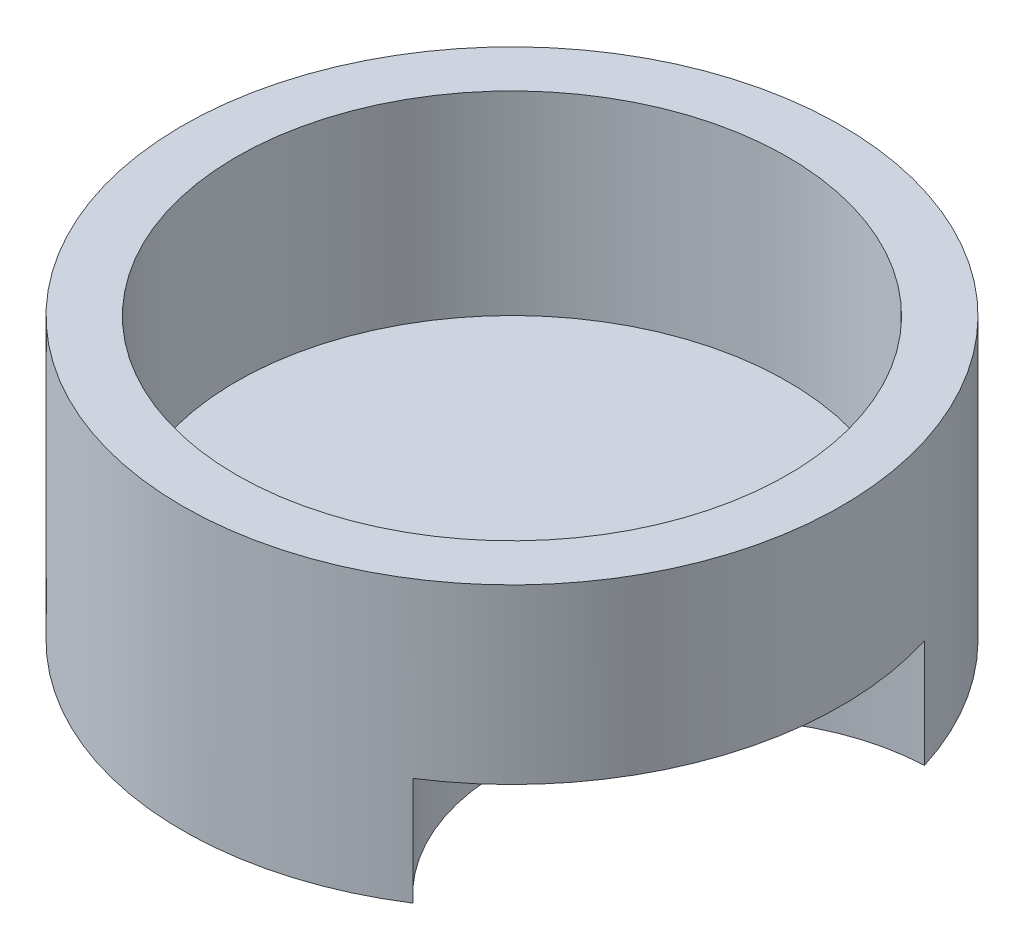
SolidWorks part; units mm, degrees
ref_plane "前视基准面" through (0, 0, 0) normal (0, 0, 1) x (1, 0, 0)
ref_plane "上视基准面" through (0, 0, 0) normal (0, 1, 0) x (1, 0, 0)
ref_plane "右视基准面" through (0, 0, 0) normal (1, 0, 0) x (0, 0, -1)
other "Configuration Table"
sketch "草图1" plane through (0, 0, 0) normal (0, 1, 0) x (1, 0, 0)
  circle A0 centre (0, 0) radius 2.55
  circle A1 centre (0, 0) radius 3.05
  dimension "D1" = 6.1
  dimension "D2" = 5.1
extrude "凸台-拉伸1" add sketch "草图1" along normal blind 1.8
sketch "草图2" plane through (0, 0, 0) normal (0, -1, 0) x (1, 0, 0)
  circle A0 centre (0, 0) radius 3.05
  circle A1 centre (0, 0) radius 3.05 construction
extrude "凸台-拉伸2" add sketch "草图2" along normal blind 0.8
sketch "草图3" plane through (0, -0.8, 0) normal (0, -1, 0) x (1, 0, 0)
  circle A0 centre (3, 1.0925) radius 2
  dimension "D1" = 4
  dimension "D2" = 3
extrude "切除-拉伸1" cut sketch "草图3" against normal blind 1
